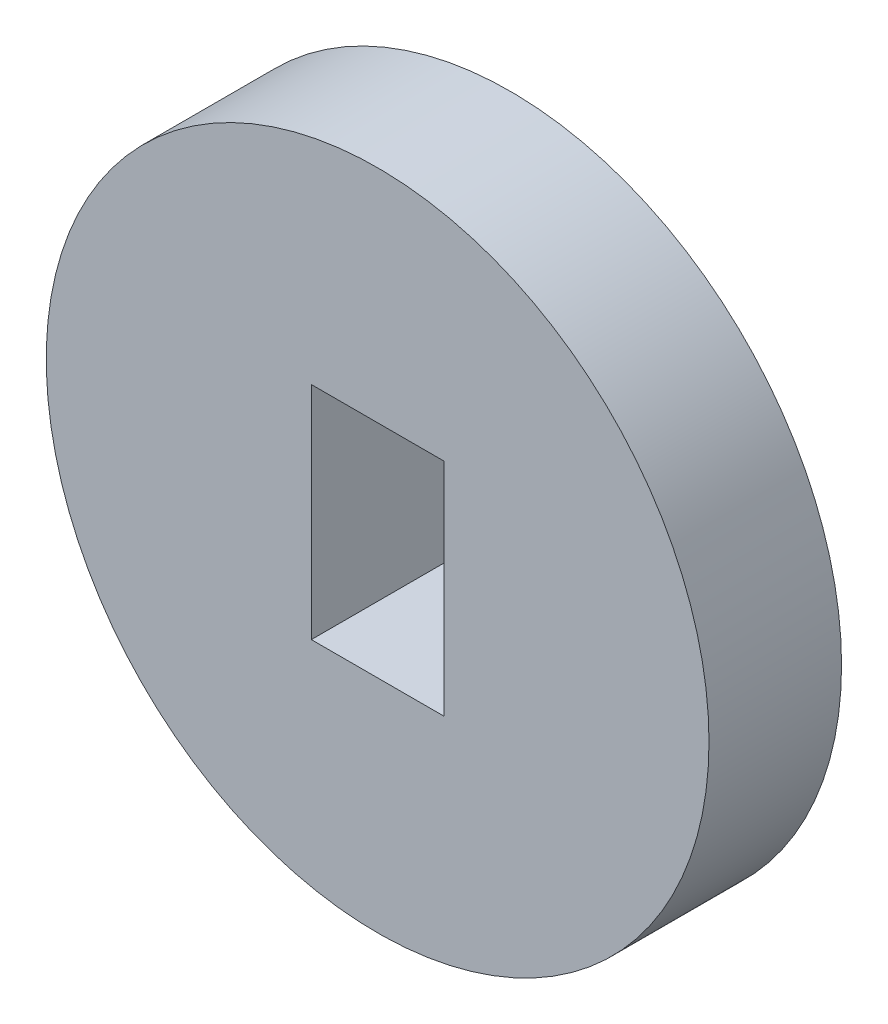
SolidWorks part; units mm, degrees
ref_plane "Plano frontal" through (0, 0, 0) normal (0, 0, 1) x (1, 0, 0)
ref_plane "Plano superior" through (0, 0, 0) normal (0, 1, 0) x (1, 0, 0)
ref_plane "Plano direito" through (0, 0, 0) normal (1, 0, 0) x (0, 0, -1)
sketch "Esboço1" plane through (0, 0, 0) normal (0, 0, 1) x (1, 0, 0)
  circle A0 centre (0, 0) radius 15
  dimension "D1" = 30
extrude "Ressalto-extrusão1" add sketch "Esboço1" along normal blind 6
sketch "Esboço2" plane through (0, 0, 6) normal (0, 0, 1) x (1, 0, 0)
  line L1 (3, -5) -> (-3, -5)
  line L2 (3, -5) -> (3, 5)
  line L3 (3, 5) -> (-3, 5)
  line L4 (-3, -5) -> (-3, 5)
  line L5 (3, -5) -> (-3, 5) construction
  line L6 (3, 5) -> (-3, -5) construction
  point P0 (0, 0)
  dimension "D1" = 10
  dimension "D2" = 6
extrude "Corte-extrusão1" cut sketch "Esboço2" against normal blind 6
